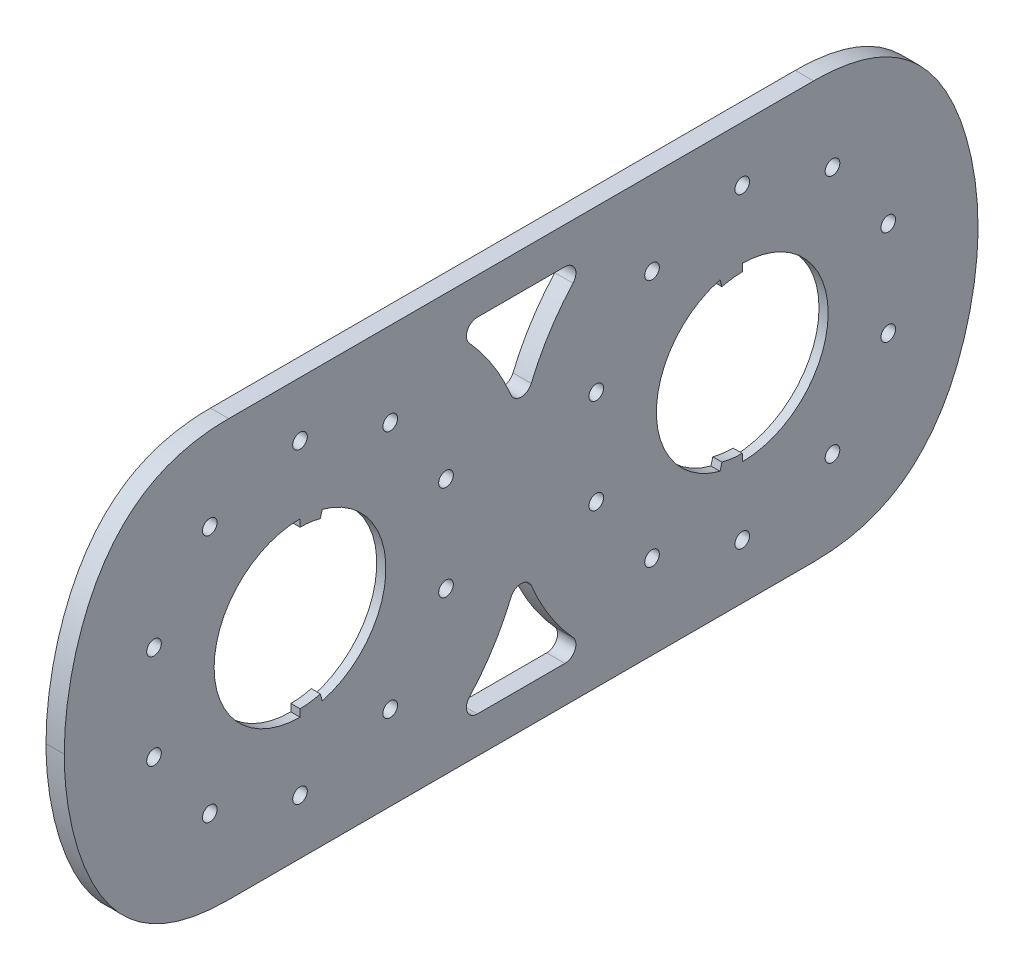
SolidWorks part; units mm, degrees
ref_plane "前视基准面" through (0, 0, 0) normal (0, 0, 1) x (1, 0, 0)
ref_plane "上视基准面" through (0, 0, 0) normal (0, 1, 0) x (1, 0, 0)
ref_plane "右视基准面" through (0, 0, 0) normal (1, 0, 0) x (0, 0, -1)
sketch "草图1" plane through (0, 0, 0) normal (1, 0, 0) x (0, 0, -1)
  line L0 (0, 57) -> (80, 57)
  line L1 (80, -57) -> (0, -57)
  line L2 (0, 57) -> (0, -57)
  line L3 (80, 57) -> (110.7152, 57) construction
  line L4 (110.7152, 57) -> (118.0231, 36.993) construction
  line L5 (118.0231, 36.993) -> (125, 20.498) construction
  line L6 (125, 20.498) -> (125, 0) construction
  line L7 (0, 0) -> (125, 0) construction
  line L8 (80, -57) -> (110.7152, -57) construction
  line L9 (110.7152, -57) -> (118.0231, -36.993) construction
  line L10 (118.0231, -36.993) -> (125, -20.498) construction
  line L11 (125, -20.498) -> (125, 0) construction
  circle A0 centre (60.5, 0) radius 48 construction
  spline S0 degree 4 poles (80, 57) (110.7152, 57) (118.0231, 36.993) (125, 20.498) (125, 0) knots 0 0 0 0 0 1 1 1 1 1
  spline S1 degree 4 poles (80, -57) (110.7152, -57) (118.0231, -36.993) (125, -20.498) (125, 0) knots 0 0 0 0 0 1 1 1 1 1
  dimension "D1" = 60.5
  dimension "D2" = 96
  dimension "D4" = 125
  dimension "D3" = 57
  dimension "D6" = 80
extrude "凸台-拉伸1" add sketch "草图1" along normal blind 5
sketch "草图2" plane through (0, 0, 0) normal (-1, 0, 0) x (0, 0, 1)
  circle A0 centre (-60.5, 0) radius 31
  dimension "D1" = 60.5
  dimension "D2" = 62
extrude "切除-拉伸1" cut sketch "草图2" against normal blind 2.5
sketch "草图3" plane through (0, 0, 0) normal (-1, 0, 0) x (0, 0, 1)
  line L0 (-60.5, 0) -> (-60.5, 79.1647) construction
  line L1 (-60.5, 0) -> (-60.5, 42) construction
  circle A1 centre (-60.5, 42) radius 2
  dimension "D1" = 0
  dimension "D2" = 42
  dimension "D3" = 4
extrude "切除-拉伸2" cut sketch "草图3" against normal up to next
pattern_circular "阵列(圆周)1" count 10 over 360 about axis through (0, 0, -60.5) along (1, 0, 0) of "切除-拉伸2"
sketch "草图4" plane through (2.5, 0, 0) normal (-1, 0, 0) x (0, 0, 1)
  circle A0 centre (-60.5, 0) radius 23.5
  dimension "D1" = 47
extrude "切除-拉伸3" cut sketch "草图4" against normal up to next
sketch "草图5" plane through (5, 0, 0) normal (1, 0, 0) x (0, 0, -1)
  circle A0 centre (60.5, 0) radius 34.5
  circle A1 centre (60.5, 0) radius 37.5
  dimension "D1" = 75
  dimension "D2" = 69
sketch "草图7" plane through (0, 0, 0) normal (-1, 0, 0) x (0, 0, 1)
  line L0 (-60.5, 48) -> (-81.7662, 48)
  line L1 (-60.5, -48) -> (-81.7662, -48)
  arc A0 (-60.5, 48) -> (-60.5, -48) centre (-60.5, 0) ccw
  arc A1 (-81.7662, 48) -> (-81.7662, -48) centre (-60.5, 0) ccw
  dimension "D1" = 96
  dimension "D2" = 105
sketch "草图8" plane through (5, 0, 0) normal (1, 0, 0) x (0, 0, -1)
  line L0 (54.9354, 20.7674) -> (54.4178, 22.6993)
  line L1 (60.5, 21.5) -> (60.5, 23.5)
  line L2 (60.5, 0) -> (0, 0) construction
  line L3 (60.5, -21.5) -> (60.5, -23.5)
  line L4 (54.9354, -20.7674) -> (54.4178, -22.6993)
  circle A0 centre (60.5, 0) radius 23.5 construction
  arc A1 (60.5, 23.5) -> (54.4178, 22.6993) centre (60.5, 0) ccw
  arc A2 (60.5, 21.5) -> (54.9354, 20.7674) centre (60.5, 0) ccw
  arc A3 (60.5, -21.5) -> (54.9354, -20.7674) centre (60.5, 0) cw
  arc A4 (60.5, -23.5) -> (54.4178, -22.6993) centre (60.5, 0) cw
  dimension "D1" = 43
  dimension "D2" = 15
extrude "凸台-拉伸3" add sketch "草图8" against normal up to surface (2.5 mm away) up to face at (2.5, 0, -37)
mirror "镜向3" about plane through (5, 57, 0) normal (0, 0, -1) of bodies 122 114
sketch "草图9" plane through (5, 0, 0) normal (1, 0, 0) x (0, 0, -1)
  circle A0 centre (0, 0) radius 13.7633
sketch "草图10" plane through (5, 0, 0) normal (1, 0, 0) x (0, 0, -1)
  line L2 (-60.5, 0) -> (60.5, 0) construction
  line L3 (80, 47) -> (-80, 47)
  line L4 (11.9794, 47) -> (-11.9794, 47)
  line L5 (11.9794, -47) -> (-11.9794, -47)
  arc A0 (-2.771, 23.9502) -> (-14.2017, 41.9847) centre (-60.5, 0) ccw
  arc A1 (14.2017, 41.9847) -> (2.771, 23.9502) centre (60.5, 0) ccw
  arc A2 (2.771, 23.9502) -> (-2.771, 23.9502) centre (0, 25.0998) cw
  arc A3 (-14.2017, 41.9847) -> (-11.9794, 47) centre (-11.9794, 44) cw
  arc A4 (14.2017, 41.9847) -> (11.9794, 47) centre (11.9794, 44) ccw
  arc A5 (14.2017, -41.9847) -> (2.771, -23.9502) centre (60.5, 0) cw
  arc A6 (2.771, -23.9502) -> (-2.771, -23.9502) centre (0, -25.0998) ccw
  arc A7 (-2.771, -23.9502) -> (-14.2017, -41.9847) centre (-60.5, 0) cw
  arc A8 (-14.2017, -41.9847) -> (-11.9794, -47) centre (-11.9794, -44) ccw
  arc A9 (14.2017, -41.9847) -> (11.9794, -47) centre (11.9794, -44) cw
  dimension "D1" = 125
  dimension "D2" = 125
  dimension "D4" = 3
  dimension "D3" = 10
extrude "切除-拉伸4" cut sketch "草图10" against normal blind 10
